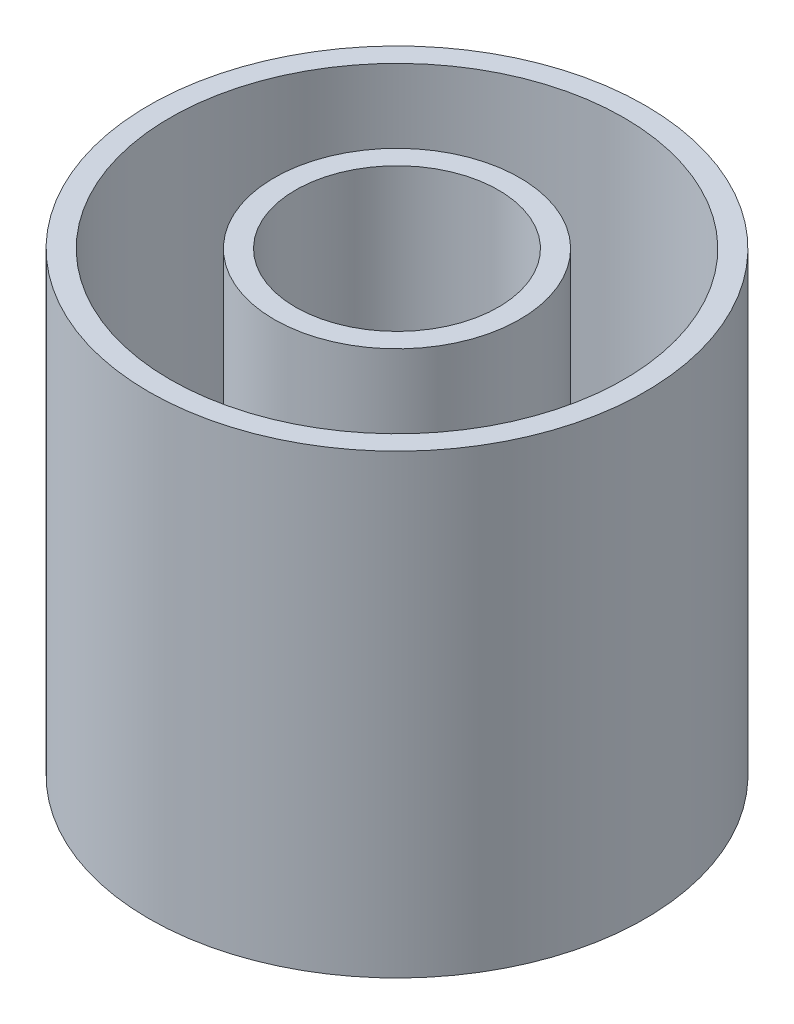
SolidWorks part; units mm, degrees
material "VITON"
ref_plane "Front Plane" through (0, 0, 0) normal (0, 0, 1) x (1, 0, 0)
ref_plane "Top Plane" through (0, 0, 0) normal (0, 1, 0) x (1, 0, 0)
ref_plane "Right Plane" through (0, 0, 0) normal (1, 0, 0) x (0, 0, -1)
sketch "Sketch1" plane through (0, 0, 0) normal (0, 1, 0) x (1, 0, 0)
  circle A0 centre (0, 0) radius 11.6459
  dimension "D1" = 23.2918
extrude "main extrusion" add sketch "Sketch1" along normal blind 21.4122 contours A0
sketch "Sketch2" plane through (0, 21.4122, 0) normal (0, 1, 0) x (1, 0, 0)
  circle A0 centre (0, 0) radius 4.7625
  dimension "D1" = 9.525
extrude "ID bore" cut sketch "Sketch2" against normal blind 20
sketch "Sketch3" plane through (0, 21.4122, 0) normal (0, 1, 0) x (1, 0, 0)
  circle A0 centre (0, 0) radius 10.6459
  circle A1 centre (0, 0) radius 5.7625
  dimension "D1" = 11.525
  dimension "D2" = 21.2918
extrude "seal recess" cut sketch "Sketch3" against normal blind 20.4122
equation "\"D1@Sketch1\" = \"lower seal OD\""
equation "\"D1@main extrusion\" = \"lower seal depth\""
equation "\"D1@Sketch2\" = \"lower seal ID\""
equation "\"motor mount pattern diameter\"= 30mm"
equation "\"D2@Sketch3\" = \"lower seal OD\" - 2mm"
equation "\"D1@Sketch3\" = \"lower seal ID\" + 2mm"
equation "\"D1@seal recess\" = \"lower seal depth\" - 1mm"
equation "\"lower seal OD\" = .917in\t\t'this is https://www.mcmaster.com/#9281k121/=174001b"
equation "\"lower seal ID\"= .375in"
equation "\"lower seal depth\" = .625in + .218in"
